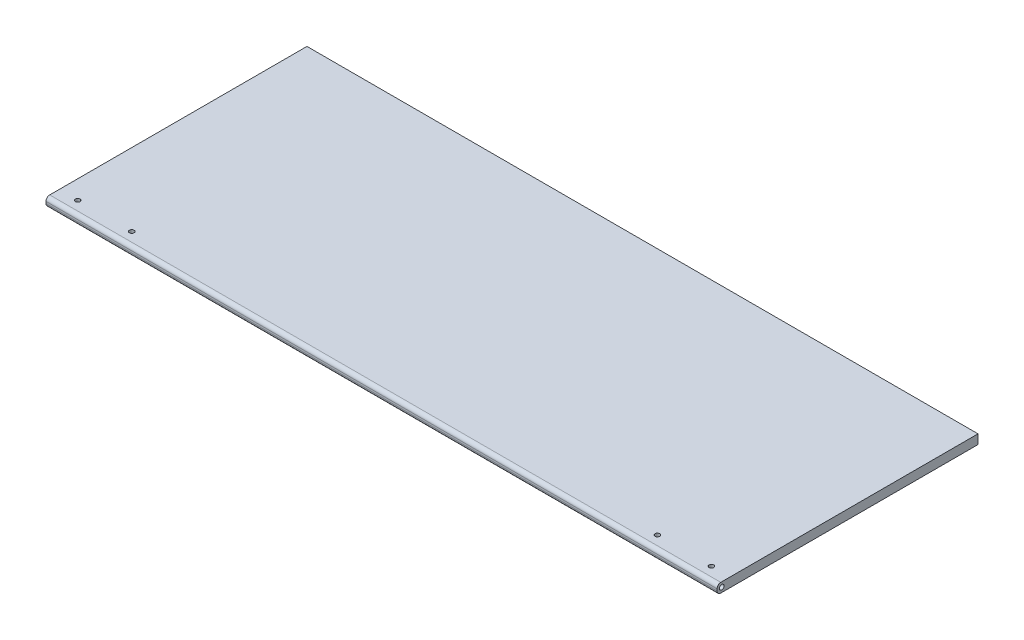
SolidWorks part; units mm, degrees
material "6061 Alloy"
ref_plane "Front Plane" through (0, 0, 0) normal (0, 0, 1) x (1, 0, 0)
ref_plane "Top Plane" through (0, 0, 0) normal (0, 1, 0) x (1, 0, 0)
ref_plane "Right Plane" through (0, 0, 0) normal (1, 0, 0) x (0, 0, -1)
sketch "Sketch1" plane through (0, 0, 0) normal (0, 1, 0) x (1, 0, 0)
  line L1 (-228.6, 88.9) -> (228.6, 88.9)
  line L2 (-228.6, 88.9) -> (-228.6, -88.9)
  line L3 (-228.6, -88.9) -> (228.6, -88.9)
  line L4 (228.6, 88.9) -> (228.6, -88.9)
  line L5 (-228.6, 88.9) -> (228.6, -88.9) construction
  line L6 (-228.6, -88.9) -> (228.6, 88.9) construction
  point P0 (0, 0)
  dimension "D1" = 177.8
  dimension "D2" = 457.2
extrude "Boss-Extrude1" add sketch "Sketch1" along normal blind 6.35
sketch "Sketch2" plane through (-228.6, 0, 0) normal (-1, 0, 0) x (0, 0, 1)
  line L0 (-88.9, 6.35) -> (88.9, 6.35) construction
  line L1 (88.9, 6.35) -> (88.9, 0) construction
  circle A0 centre (85.725, 3.175) radius 1.5875
  dimension "D1" = 3.175
  dimension "D2" = 3.175
  dimension "D3" = 3.175
extrude "Cut-Extrude1" cut sketch "Sketch2" against normal through all
fillet "Fillet1" radius 2.54 2 edges at (0, 0, 88.9) (0, 6.35, 88.9)
sketch "Sketch3" plane through (228.6, 0, 0) normal (1, 0, 0) x (0, 0, -1)
  line L0 (88.9, 6.35) -> (88.9, 0) construction
  line L1 (-48.26, 4.572) -> (-33.02, 4.572)
  line L2 (-48.26, 4.572) -> (-48.26, 1.27)
  line L3 (-48.26, 1.27) -> (-33.02, 1.27)
  line L4 (-33.02, 4.572) -> (-33.02, 1.27)
  line L5 (-48.26, 4.572) -> (-33.02, 1.27) construction
  line L6 (-48.26, 1.27) -> (-33.02, 4.572) construction
  line L7 (-86.36, 0) -> (88.9, 0) construction
  point P0 (-40.64, 2.921)
  dimension "D1" = 15.24
  dimension "D2" = 129.54
  dimension "D3" = 3.302
  dimension "D4" = 1.27
sketch "Sketch4" plane through (0, 0, 0) normal (0, -1, 0) x (1, 0, 0)
  line L0 (228.6, 86.36) -> (-228.6, 86.36) construction
  line L1 (-228.6, -88.9) -> (-228.6, 86.36) construction
  circle A0 centre (-179.07, 80.01) radius 1.5875
  circle A1 centre (-215.9, 80.01) radius 1.5875
  dimension "D2" = 3.175
  dimension "D1" = 6.35
  dimension "D3" = 36.83
  dimension "D4" = 12.7
extrude "Cut-Extrude3" cut sketch "Sketch4" against normal through all
mirror "Mirror1" about plane through (0, 0, 0) normal (1, 0, 0) of "Cut-Extrude3"
